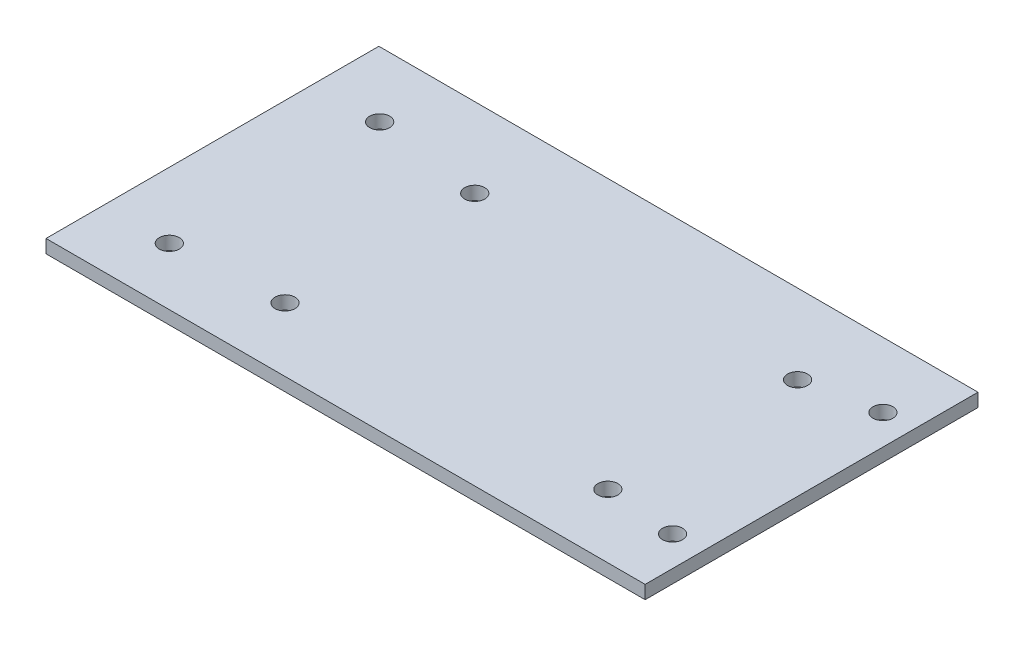
SolidWorks part; units mm, degrees
ref_plane "前视基准面" through (0, 0, 0) normal (0, 0, 1) x (1, 0, 0)
ref_plane "上视基准面" through (0, 0, 0) normal (0, 1, 0) x (1, 0, 0)
ref_plane "右视基准面" through (0, 0, 0) normal (1, 0, 0) x (0, 0, -1)
sketch "草图1" plane through (0, 0, 0) normal (0, 1, 0) x (1, 0, 0)
  line L1 (0, 0) -> (90, 0)
  line L2 (0, 0) -> (0, 50)
  line L3 (0, 50) -> (90, 50)
  line L4 (90, 0) -> (90, 50)
  circle A0 centre (26.3346, 38.0677) radius 1.5
  circle A1 centre (74.8346, 38.0677) radius 1.5
  circle A2 centre (74.8346, 9.5677) radius 1.5
  circle A3 centre (26.3346, 9.5677) radius 1.5
  circle A4 centre (9.8994, 40.2217) radius 1.5
  circle A5 centre (85.4994, 40.2217) radius 1.5
  circle A6 centre (85.4994, 8.6217) radius 1.5
  circle A7 centre (9.8994, 8.6217) radius 1.5
  point P15 (9.8994, 40.2217)
  point P16 (25.1778, 37.9927)
  point P17 (26.3346, 38.0677)
  dimension "D3" = 3
  dimension "D6" = 3
  dimension "D1" = 50
  dimension "D2" = 90
  dimension "D4" = 2
  dimension "D5" = 2
  dimension "D7" = 2
  dimension "D8" = 2
extrude "凸台-拉伸1" add sketch "草图1" along normal blind 2
